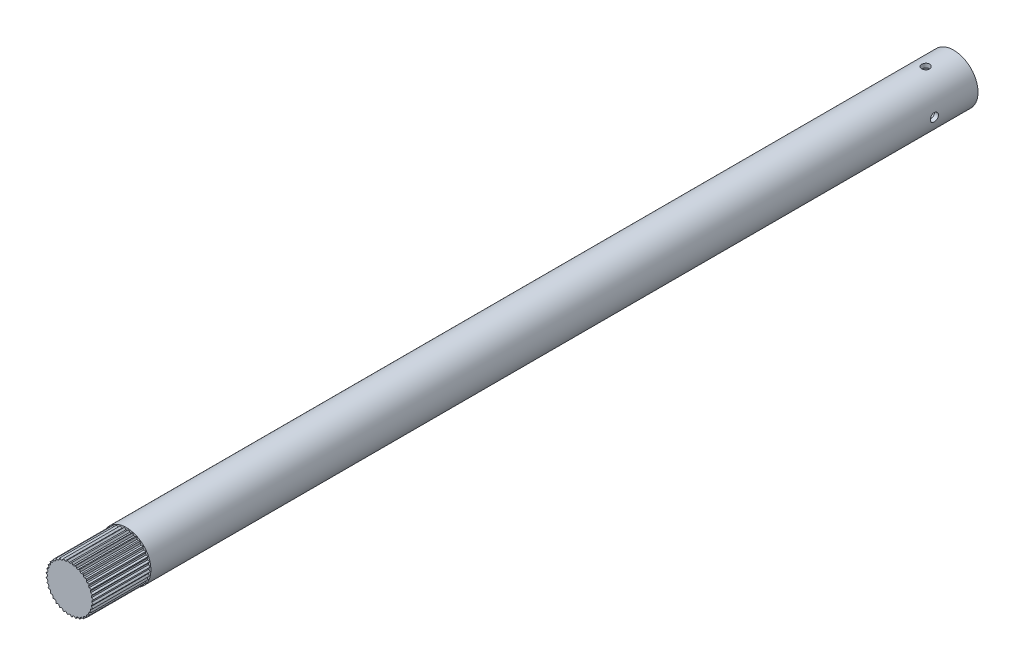
SolidWorks part; units mm, degrees
material "AISI 1015 Steel, Cold Drawn (SS)"
ref_plane "X-Y Datum" through (0, 0, 0) normal (0, 0, 1) x (1, 0, 0)
ref_plane "X-Z Datum" through (0, 0, 0) normal (0, 1, 0) x (1, 0, 0)
ref_plane "Y-Z Datum" through (0, 0, 0) normal (1, 0, 0) x (0, 0, -1)
sketch "Sketch9" plane through (0, 0, 0) normal (0, 1, 0) x (1, 0, 0)
  line L0 (16.002, 0) -> (0, 0)
  line L1 (0, 0) -> (0, -389.0916)
  line L2 (0, -389.0916) -> (-72.2493, -524.9728)
  dimension "D1" = 153.895
  dimension "D2" = 28
  dimension "D3" = 389.0916
  dimension "D5" = 16.002
sketch "Sketch5" plane through (0, 0, 0) normal (0, 1, 0) x (1, 0, 0)
  line L0 (7.9375, -367.5016) -> (7.9375, -22.1615)
  line L1 (7.9375, -22.1615) -> (9.525, -22.1615)
  line L2 (9.525, -22.1615) -> (9.525, -367.5016)
  line L3 (9.525, -367.5016) -> (7.9375, -367.5016)
  line L5 (16.002, 0) -> (0, 0) construction
  line L6 (0, 0) -> (0, -389.0916) construction
  line L7 (0, -389.0916) -> (9.525, -389.0916) construction
  line L8 (12.5602, -369.8416) -> (0, -369.8416) construction
  dimension "D1" = 1.5875
  dimension "D2" = 22.1615
  dimension "D3" = 7.9375
  dimension "D4" = 19.25
  dimension "D5" = 21.59
revolve "Revolve2" add sketch "Sketch5" angle 360 about L1
sketch "Sketch6" plane through (0, 0, 0) normal (0, 1, 0) x (1, 0, 0)
  circle A0 centre (0, -33.1635) radius 1.5875 construction
  circle A1 centre (0, -33.1635) radius 1.5875
sketch "Sketch7" plane through (0, 0, 0) normal (1, 0, 0) x (0, 0, -1)
  circle A2 centre (-39.196, 0) radius 1.5875
  circle A4 centre (-39.196, 0) radius 1.5875 construction
extrude "Cut-Extrude5" cut sketch "Sketch7" against normal through all both and the other way through all
extrude "Cut-Extrude6" cut sketch "Sketch6" against normal through all both and the other way through all
sketch "Sketch8" plane through (0, 0, 0) normal (0, 0, 1) x (1, 0, 0)
  line L0 (9.2357, -0.808) -> (8.6817, -0.254)
  line L1 (8.6817, -0.254) -> (8.6817, 0.254)
  line L2 (8.6817, 0.254) -> (9.2357, 0.808)
  line L3 (8.6817, 0) -> (0, 0) construction
  line L4 (8.9551, -2.3995) -> (8.5057, -1.7577)
  line L5 (8.5057, -1.7577) -> (8.5939, -1.2574)
  line L6 (8.5939, -1.2574) -> (9.2357, -0.808)
  line L7 (8.4024, -3.9181) -> (8.0713, -3.208)
  line L8 (8.0713, -3.208) -> (8.245, -2.7306)
  line L9 (8.245, -2.7306) -> (8.9551, -2.3995)
  line L10 (7.5944, -5.3176) -> (7.3916, -4.5608)
  line L11 (7.3916, -4.5608) -> (7.6456, -4.1209)
  line L12 (7.6456, -4.1209) -> (8.4024, -3.9181)
  line L13 (6.5556, -6.5556) -> (6.4873, -5.7751)
  line L14 (6.4873, -5.7751) -> (6.8138, -5.3859)
  line L15 (6.8138, -5.3859) -> (7.5944, -5.3176)
  line L16 (5.3176, -7.5944) -> (5.3859, -6.8138)
  line L17 (5.3859, -6.8138) -> (5.7751, -6.4873)
  line L18 (5.7751, -6.4873) -> (6.5556, -6.5556)
  line L19 (3.9181, -8.4024) -> (4.1209, -7.6456)
  line L20 (4.1209, -7.6456) -> (4.5608, -7.3916)
  line L21 (4.5608, -7.3916) -> (5.3176, -7.5944)
  line L22 (2.3995, -8.9551) -> (2.7306, -8.245)
  line L23 (2.7306, -8.245) -> (3.208, -8.0713)
  line L24 (3.208, -8.0713) -> (3.9181, -8.4024)
  line L25 (0.808, -9.2357) -> (1.2574, -8.5939)
  line L26 (1.2574, -8.5939) -> (1.7577, -8.5057)
  line L27 (1.7577, -8.5057) -> (2.3995, -8.9551)
  line L28 (-0.808, -9.2357) -> (-0.254, -8.6817)
  line L29 (-0.254, -8.6817) -> (0.254, -8.6817)
  line L30 (0.254, -8.6817) -> (0.808, -9.2357)
  line L31 (-2.3995, -8.9551) -> (-1.7577, -8.5057)
  line L32 (-1.7577, -8.5057) -> (-1.2574, -8.5939)
  line L33 (-1.2574, -8.5939) -> (-0.808, -9.2357)
  line L34 (-3.9181, -8.4024) -> (-3.208, -8.0713)
  line L35 (-3.208, -8.0713) -> (-2.7306, -8.245)
  line L36 (-2.7306, -8.245) -> (-2.3995, -8.9551)
  line L37 (-5.3176, -7.5944) -> (-4.5608, -7.3916)
  line L38 (-4.5608, -7.3916) -> (-4.1209, -7.6456)
  line L39 (-4.1209, -7.6456) -> (-3.9181, -8.4024)
  line L40 (-6.5556, -6.5556) -> (-5.7751, -6.4873)
  line L41 (-5.7751, -6.4873) -> (-5.3859, -6.8138)
  line L42 (-5.3859, -6.8138) -> (-5.3176, -7.5944)
  line L43 (-7.5944, -5.3176) -> (-6.8138, -5.3859)
  line L44 (-6.8138, -5.3859) -> (-6.4873, -5.7751)
  line L45 (-6.4873, -5.7751) -> (-6.5556, -6.5556)
  line L46 (-8.4024, -3.9181) -> (-7.6456, -4.1209)
  line L47 (-7.6456, -4.1209) -> (-7.3916, -4.5608)
  line L48 (-7.3916, -4.5608) -> (-7.5944, -5.3176)
  line L49 (-8.9551, -2.3995) -> (-8.245, -2.7306)
  line L50 (-8.245, -2.7306) -> (-8.0713, -3.208)
  line L51 (-8.0713, -3.208) -> (-8.4024, -3.9181)
  line L52 (-9.2357, -0.808) -> (-8.5939, -1.2574)
  line L53 (-8.5939, -1.2574) -> (-8.5057, -1.7577)
  line L54 (-8.5057, -1.7577) -> (-8.9551, -2.3995)
  line L55 (-9.2357, 0.808) -> (-8.6817, 0.254)
  line L56 (-8.6817, 0.254) -> (-8.6817, -0.254)
  line L57 (-8.6817, -0.254) -> (-9.2357, -0.808)
  line L58 (-8.9551, 2.3995) -> (-8.5057, 1.7577)
  line L59 (-8.5057, 1.7577) -> (-8.5939, 1.2574)
  line L60 (-8.5939, 1.2574) -> (-9.2357, 0.808)
  line L61 (-8.4024, 3.9181) -> (-8.0713, 3.208)
  line L62 (-8.0713, 3.208) -> (-8.245, 2.7306)
  line L63 (-8.245, 2.7306) -> (-8.9551, 2.3995)
  line L64 (-7.5944, 5.3176) -> (-7.3916, 4.5608)
  line L65 (-7.3916, 4.5608) -> (-7.6456, 4.1209)
  line L66 (-7.6456, 4.1209) -> (-8.4024, 3.9181)
  line L67 (-6.5556, 6.5556) -> (-6.4873, 5.7751)
  line L68 (-6.4873, 5.7751) -> (-6.8138, 5.3859)
  line L69 (-6.8138, 5.3859) -> (-7.5944, 5.3176)
  line L70 (-5.3176, 7.5944) -> (-5.3859, 6.8138)
  line L71 (-5.3859, 6.8138) -> (-5.7751, 6.4873)
  line L72 (-5.7751, 6.4873) -> (-6.5556, 6.5556)
  line L73 (-3.9181, 8.4024) -> (-4.1209, 7.6456)
  line L74 (-4.1209, 7.6456) -> (-4.5608, 7.3916)
  line L75 (-4.5608, 7.3916) -> (-5.3176, 7.5944)
  line L76 (-2.3995, 8.9551) -> (-2.7306, 8.245)
  line L77 (-2.7306, 8.245) -> (-3.208, 8.0713)
  line L78 (-3.208, 8.0713) -> (-3.9181, 8.4024)
  line L79 (-0.808, 9.2357) -> (-1.2574, 8.5939)
  line L80 (-1.2574, 8.5939) -> (-1.7577, 8.5057)
  line L81 (-1.7577, 8.5057) -> (-2.3995, 8.9551)
  line L82 (0.808, 9.2357) -> (0.254, 8.6817)
  line L83 (0.254, 8.6817) -> (-0.254, 8.6817)
  line L84 (-0.254, 8.6817) -> (-0.808, 9.2357)
  line L85 (2.3995, 8.9551) -> (1.7577, 8.5057)
  line L86 (1.7577, 8.5057) -> (1.2574, 8.5939)
  line L87 (1.2574, 8.5939) -> (0.808, 9.2357)
  line L88 (3.9181, 8.4024) -> (3.208, 8.0713)
  line L89 (3.208, 8.0713) -> (2.7306, 8.245)
  line L90 (2.7306, 8.245) -> (2.3995, 8.9551)
  line L91 (5.3176, 7.5944) -> (4.5608, 7.3916)
  line L92 (4.5608, 7.3916) -> (4.1209, 7.6456)
  line L93 (4.1209, 7.6456) -> (3.9181, 8.4024)
  line L94 (6.5556, 6.5556) -> (5.7751, 6.4873)
  line L95 (5.7751, 6.4873) -> (5.3859, 6.8138)
  line L96 (5.3859, 6.8138) -> (5.3176, 7.5944)
  line L97 (7.5944, 5.3176) -> (6.8138, 5.3859)
  line L98 (6.8138, 5.3859) -> (6.4873, 5.7751)
  line L99 (6.4873, 5.7751) -> (6.5556, 6.5556)
  line L100 (8.4024, 3.9181) -> (7.6456, 4.1209)
  line L101 (7.6456, 4.1209) -> (7.3916, 4.5608)
  line L102 (7.3916, 4.5608) -> (7.5944, 5.3176)
  line L103 (8.9551, 2.3995) -> (8.245, 2.7306)
  line L104 (8.245, 2.7306) -> (8.0713, 3.208)
  line L105 (8.0713, 3.208) -> (8.4024, 3.9181)
  line L106 (9.2357, 0.808) -> (8.5939, 1.2574)
  line L107 (8.5939, 1.2574) -> (8.5057, 1.7577)
  line L108 (8.5057, 1.7577) -> (8.9551, 2.3995)
  circle A0 centre (0, 0) radius 12.7
  circle A1 centre (0, 0) radius 9.271 construction
  circle A2 centre (0, 0) radius 8.6854 construction
  point P153 (0, 0)
  dimension "D1" = 25.4
  dimension "D4" = 18.542
  dimension "D6" = 17.3708
  dimension "D2" = 0.508
  dimension "D3" = 135
  dimension "D5" = 36
extrude "Cut-Extrude7" cut sketch "Sketch8" against normal blind 22.225 from surface at 367.5016 starting at face at (-9.525, 0, 367.5016)
ref_plane "Plane1" through (0, 0, 47.5615) normal (0, 0, -1) x (-1, 0, 0)
sketch "Sketch10" plane through (0, 0, 47.5615) normal (0, 0, -1) x (-1, 0, 0)
  circle A0 centre (0, 0) radius 7.9375
  dimension "D1" = 15.875
extrude "Boss-Extrude1" add sketch "Sketch10" against normal up to surface (319.9401 mm away) up to face at (-7.9375, 0, 367.5016)
sketch "Sketch11" plane through (0, 0, 22.1615) normal (0, 0, -1) x (-1, 0, 0)
  line L0 (0, 9.525) -> (13.3548, 9.525) construction
  line L1 (0, 9.525) -> (0, 15.4312) construction
  line L2 (-9.525, 0) -> (-9.525, 9.1744) construction
  line L3 (-9.525, 0) -> (-16.674, 0) construction
  circle A0 centre (0, 0) radius 9.525 construction
  point P0 (0, 9.525)
  point P1 (-9.525, 0)
